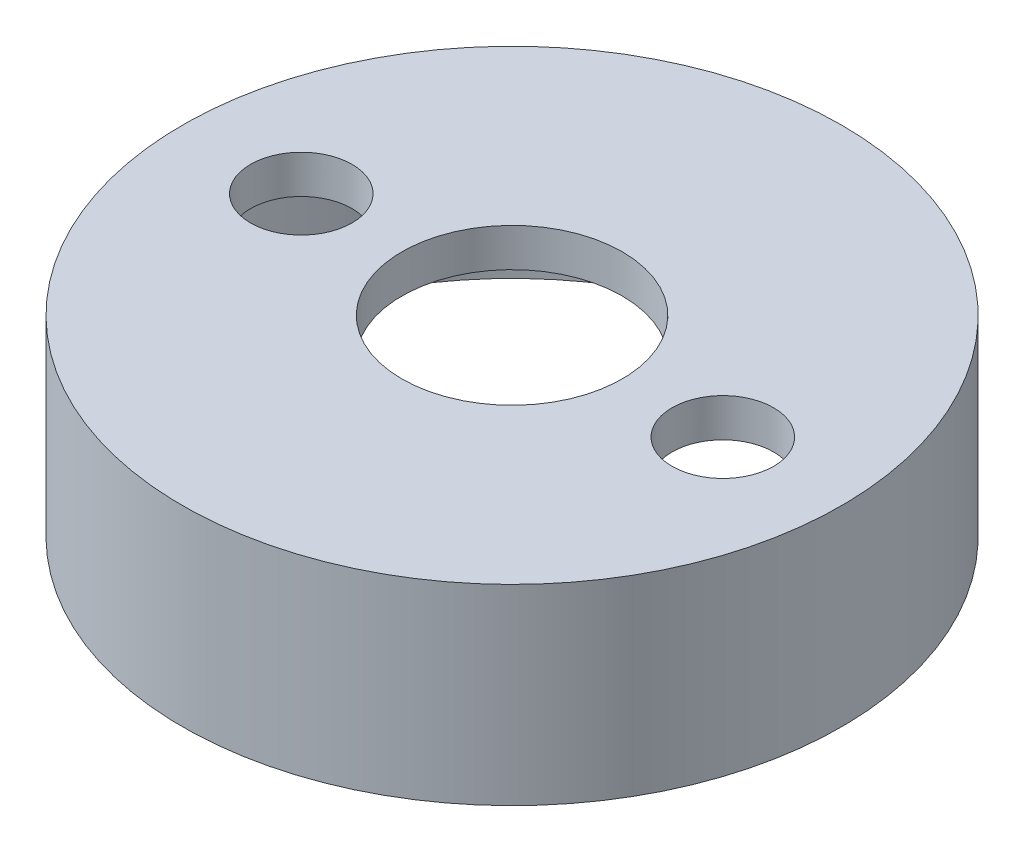
SolidWorks part; units mm, degrees
ref_plane "Front" through (0, 0, 0) normal (0, 0, 1) x (1, 0, 0)
ref_plane "Top" through (0, 0, 0) normal (0, 1, 0) x (1, 0, 0)
ref_plane "Right" through (0, 0, 0) normal (1, 0, 0) x (0, 0, -1)
sketch "Sketch1" plane through (0, 0, 0) normal (0, 0, 1) x (1, 0, 0)
  line L0 (0, -9.2601) -> (0, 11.5631) construction
  line L1 (5.75, 10) -> (17.2, 10)
  line L2 (17.2, 10) -> (17.2, 0)
  line L3 (17.2, 0) -> (16.5, 0)
  line L4 (16.5, 0) -> (16.5, 8)
  line L5 (16.5, 8) -> (5.75, 8)
  line L6 (5.75, 8) -> (5.75, 10)
  dimension "D1" = 5.75
  dimension "D2" = 16.5
  dimension "D3" = 17.2
  dimension "D4" = 10
  dimension "D5" = 2
revolve "Revolve1" add sketch "Sketch1" angle 360 about L0
sketch "Sketch2" plane through (0, 8, 0) normal (0, -1, 0) x (1, 0, 0)
  circle A0 centre (-11, 0) radius 2.65
  circle A1 centre (11, 0) radius 2.65
  dimension "D1" = 5.3
  dimension "D2" = 11
  dimension "D3" = 11
extrude "Cut-Extrude1" cut sketch "Sketch2" against normal blind 10
